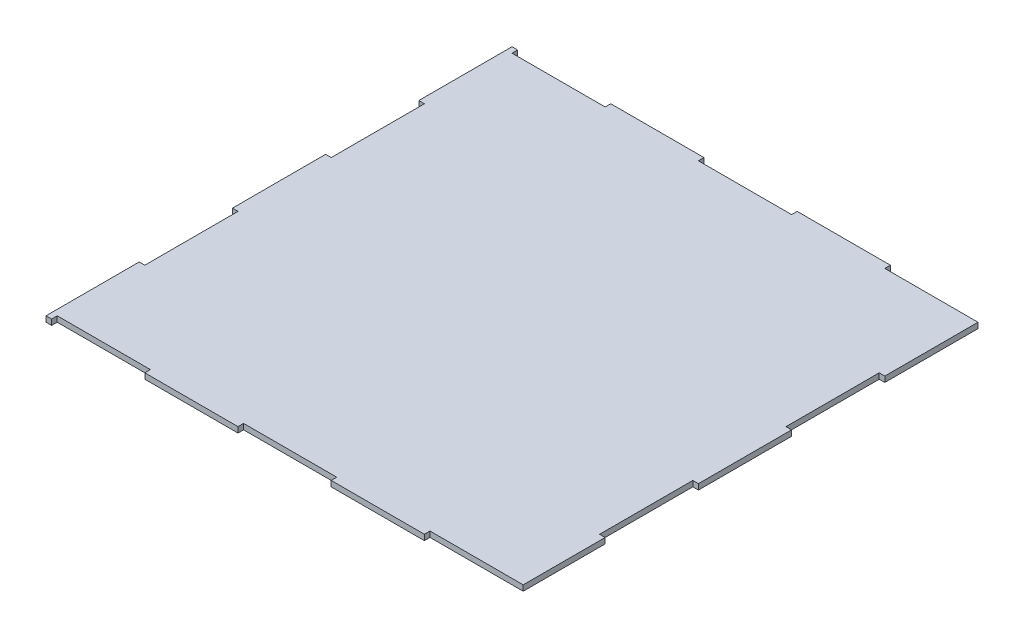
SolidWorks part; units mm, degrees
ref_plane "Front Plane" through (0, 0, 0) normal (0, 0, 1) x (1, 0, 0)
ref_plane "Top Plane" through (0, 0, 0) normal (0, 1, 0) x (1, 0, 0)
ref_plane "Right Plane" through (0, 0, 0) normal (1, 0, 0) x (0, 0, -1)
sketch "Sketch1" plane through (0, 0, 0) normal (0, 1, 0) x (1, 0, 0)
  line L0 (253, -53) -> (253, -3)
  line L1 (0, -250) -> (3, -250)
  line L2 (0, 0) -> (0, -50)
  line L3 (0, 0) -> (3, 0)
  line L4 (53, 0) -> (53, -3)
  line L5 (0, -100) -> (0, -150)
  line L6 (103, 0) -> (103, -3)
  line L7 (53, 0) -> (103, 0)
  line L8 (153, -3) -> (153, 0)
  line L9 (253, -53) -> (250, -53)
  line L10 (253, -153) -> (253, -103)
  line L11 (253, -103) -> (250, -103)
  line L12 (250, -53) -> (250, -103)
  line L13 (250, -153) -> (253, -153)
  line L14 (203, -247) -> (203, -250)
  line L15 (153, -250) -> (203, -250)
  line L16 (250, -153) -> (250, -203)
  line L17 (0, -50) -> (3, -50)
  line L18 (3, -200) -> (0, -200)
  line L19 (0, -100) -> (3, -100)
  line L20 (3, -50) -> (3, -100)
  line L21 (250, -203) -> (253, -203)
  line L22 (53, -247) -> (53, -250)
  line L23 (103, -250) -> (53, -250)
  line L24 (253, -247) -> (253, -203)
  line L25 (103, -250) -> (103, -247)
  line L26 (203, 0) -> (203, -3)
  line L27 (153, 0) -> (203, 0)
  line L28 (103, -247) -> (153, -247)
  line L33 (0, -150) -> (3, -150)
  line L34 (153, -250) -> (153, -247)
  line L35 (0, -200) -> (0, -250)
  line L36 (3, -150) -> (3, -200)
  line L62 (53, -3) -> (3, -3)
  line L63 (3, 0) -> (3, -3)
  line L64 (203, -247) -> (253, -247)
  line L66 (203, -3) -> (253, -3)
  line L67 (103, -3) -> (153, -3)
  line L75 (3, -250) -> (3, -247)
  line L78 (3, -247) -> (53, -247)
  dimension "D3" = 50
  dimension "D5" = 50
  dimension "D6" = 50
  dimension "D7" = 50
  dimension "D8" = 3
  dimension "D9" = 50
  dimension "D10" = 50
  dimension "D11" = 50
  dimension "D12" = 3
  dimension "D13" = 50
  dimension "D14" = 50
  dimension "D15" = 3
  dimension "D16" = 3
  dimension "D17" = 50
  dimension "D18" = 3
  dimension "D19" = 3
  dimension "D20" = 50
  dimension "D21" = 50
  dimension "D22" = 50
  dimension "D23" = 50
  dimension "D24" = 50
  dimension "D25" = 250
  dimension "D26" = 50
  dimension "D27" = 50
  dimension "D28" = 50
  dimension "D29" = 44
  dimension "D31" = 3
  dimension "D32" = 3
  dimension "D35" = 3
  dimension "D40" = 50
  dimension "D41" = 3
extrude "Boss-Extrude1" add sketch "Sketch1" along normal blind 3
equation "\"w\"=3"
equation "\"L\"=50"
